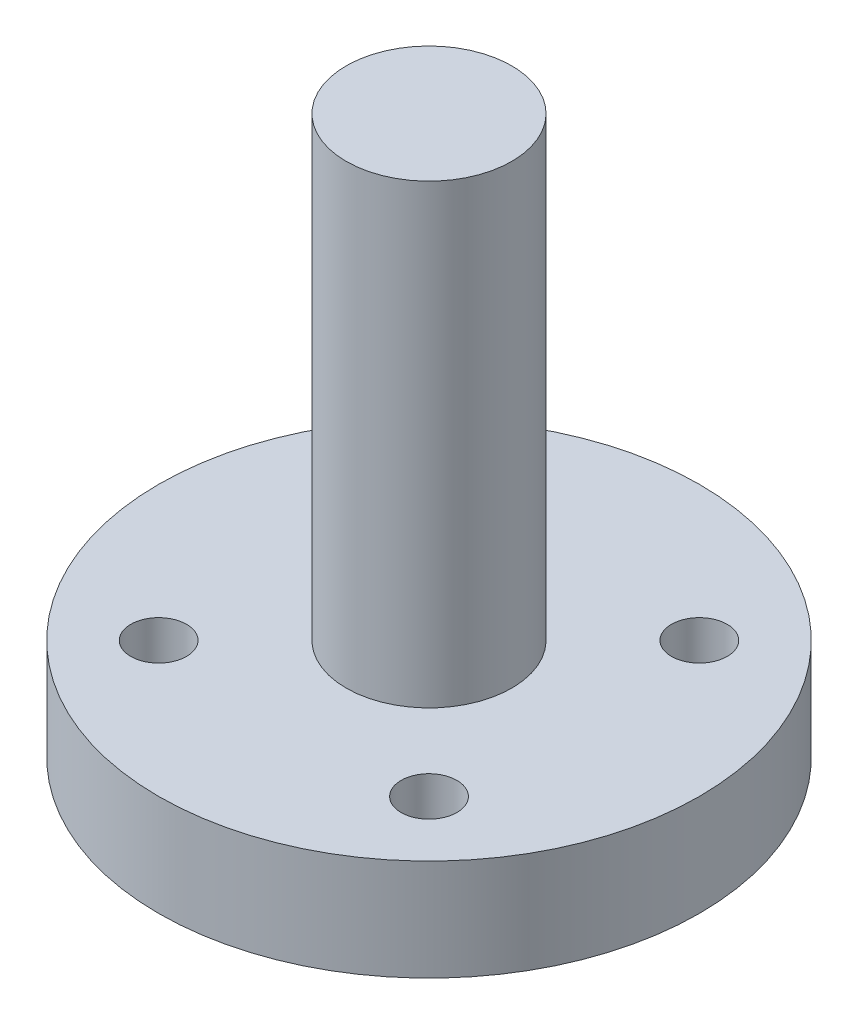
SolidWorks part; units mm, degrees
material "6061 Alloy"
ref_plane "Front Plane" through (0, 0, 0) normal (0, 0, 1) x (1, 0, 0)
ref_plane "Top Plane" through (0, 0, 0) normal (0, 1, 0) x (1, 0, 0)
ref_plane "Right Plane" through (0, 0, 0) normal (1, 0, 0) x (0, 0, -1)
sketch "Sketch1" plane through (0, 0, 0) normal (0, 1, 0) x (1, 0, 0)
  circle A0 centre (0, 0) radius 16
  dimension "D1" = 32
extrude "Boss-Extrude1" add sketch "Sketch1" along normal blind 6
sketch "Sketch3" plane through (0, 6, 0) normal (0, 1, 0) x (1, 0, 0)
  circle A1 centre (0, 0) radius 4.9
  dimension "D2" = 9.8
sketch "Sketch4" plane through (0, 0, 0) normal (0, -1, 0) x (1, 0, 0)
  line L1 (8, 8) -> (-8, 8) construction
  line L2 (8, 8) -> (8, -8) construction
  line L3 (8, -8) -> (-8, -8) construction
  line L4 (-8, 8) -> (-8, -8) construction
  line L5 (8, 8) -> (-8, -8) construction
  line L6 (8, -8) -> (-8, 8) construction
  point P0 (0, 0)
  dimension "D1" = 16
  dimension "D2" = 90
hole_wizard "Tap Drill for M4x0.7 Tap1" positions "Sketch5" profile "Sketch6" hole size "M4x0.7" standard "ANSI Metric" end condition through all
sketch "Sketch5" plane through (0, 0, 0) normal (0, -1, 0) x (-1, 0, 0)
  point P0 (-8, 8)
  point P3 (-8, -8)
  point P6 (8, -8)
  point P9 (8, 8)
sketch "Sketch6" plane through (8, 0, -8) normal (1, 0, 0) x (0, 0, -1)
  line L0 (0, 0) -> (0, 6)
  line L1 (0, 6) -> (1.65, 6)
  line L2 (1.65, 6) -> (1.65, 0)
  line L5 (1.65, 0) -> (0, 0)
  line L11 (0, -6.35) -> (0, 107.95) construction
  dimension "Thru Hole Dia." = 3.3
  dimension "Thru Hole Depth" = 6
extrude "Boss-Extrude2" add sketch "Sketch3" along normal blind 27
